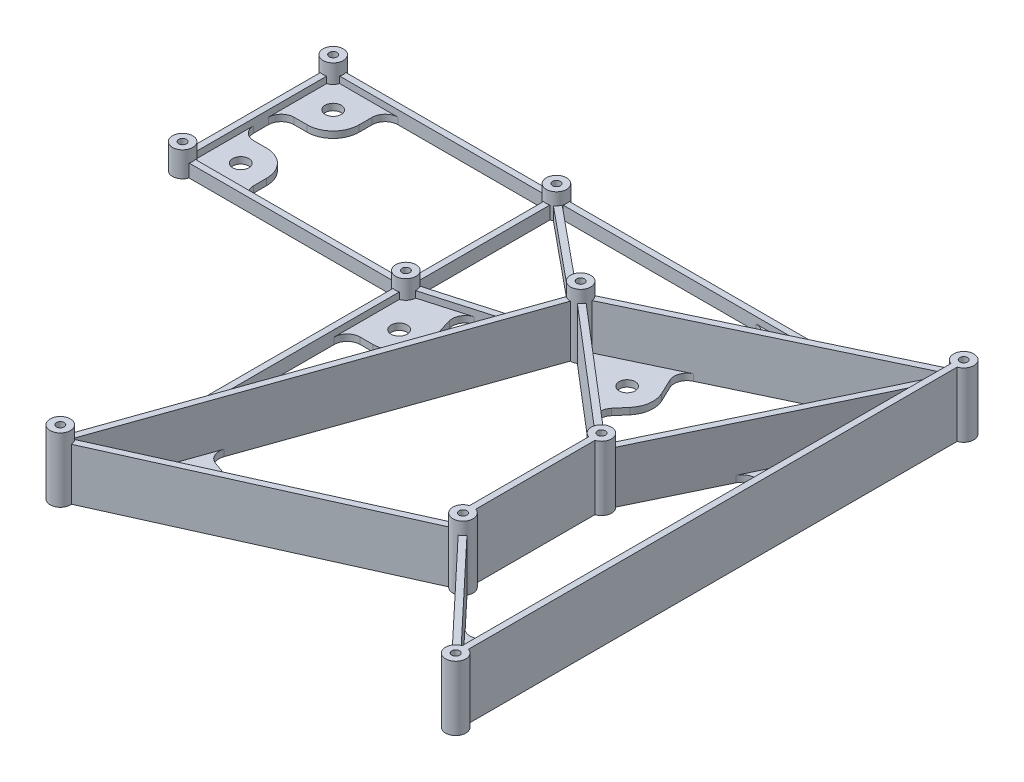
SolidWorks part; units mm, degrees
ref_plane "Front Plane" through (0, 0, 0) normal (0, 0, 1) x (1, 0, 0)
ref_plane "Top Plane" through (0, 0, 0) normal (0, 1, 0) x (1, 0, 0)
ref_plane "Right Plane" through (0, 0, 0) normal (1, 0, 0) x (0, 0, -1)
sketch "Sketch1" plane through (0, 0, 0) normal (0, 1, 0) x (1, 0, 0)
  line L0 (106.9742, -89.6492) -> (106.9742, -142.975) construction
  line L7 (0, -191.1) -> (152.3, -191.1)
  line L8 (152.3, -191.1) -> (152.3, 4.565) construction
  line L9 (106.9742, -89.6492) -> (106.9742, -142.975) construction
  line L10 (0, -191.1) -> (106.9742, -142.975) construction
  line L11 (106.9742, -142.975) -> (152.3, -191.1) construction
  line L12 (52.3, -42.975) -> (106.9742, -89.6492) construction
  line L13 (106.9742, -89.6492) -> (152.3, 4.565) construction
  line L14 (152.3, 4.565) -> (52.3, -42.975) construction
  line L15 (52.3, -42.975) -> (0, -191.1) construction
  line L16 (0, -192.3) -> (152.3, -192.3) construction
  line L17 (0.4923, -192.1944) -> (107.4665, -144.0694)
  line L18 (106.1006, -143.7977) -> (151.4264, -191.9227)
  line L19 (105.7742, -89.6492) -> (105.7742, -142.975)
  line L20 (153.5, -191.1) -> (153.5, 4.565)
  line L21 (108.0556, -90.1694) -> (153.3814, 4.0448)
  line L22 (151.7848, 5.6488) -> (51.7848, -41.8912)
  line L23 (51.5209, -43.8877) -> (106.1951, -90.5619)
  line L24 (51.1685, -42.5755) -> (-1.1315, -190.7005)
  line L25 (0, -189.9) -> (152.3, -189.9) construction
  line L26 (-0.4923, -190.0056) -> (106.4819, -141.8806)
  line L27 (107.8478, -142.1523) -> (153.1736, -190.2773)
  line L28 (108.1742, -89.6492) -> (108.1742, -142.975)
  line L29 (151.1, -191.1) -> (151.1, 4.565)
  line L30 (105.8928, -89.129) -> (151.2186, 5.0852)
  line L31 (152.8152, 3.4812) -> (52.8152, -44.0588)
  line L32 (53.0791, -42.0623) -> (107.7533, -88.7365)
  line L33 (53.4315, -43.3745) -> (1.1315, -191.4995)
  circle A1 centre (0, 0) radius 3.9 construction
  circle A2 centre (52.3, -42.975) radius 1.5
  circle A3 centre (152.3, 4.565) radius 1.5
  circle A4 centre (152.3, -191.1) radius 1.5
  circle A5 centre (0, -191.1) radius 1.5
  circle A6 centre (106.9742, -89.6492) radius 1.5
  circle A7 centre (106.9742, -142.975) radius 1.5
  circle A8 centre (106.9742, -89.6492) radius 3.9
  circle A9 centre (106.9742, -142.975) radius 3.9
  circle A10 centre (152.3, -191.1) radius 3.9
  circle A11 centre (0, -191.1) radius 3.9
  circle A12 centre (52.3, -42.975) radius 3.9
  circle A13 centre (152.3, 4.565) radius 3.9
  dimension "D11" = 3
  dimension "D2" = 4.565
  dimension "D3" = 195.665
  dimension "D4" = 152.3
  dimension "D5" = 52.3
  dimension "D6" = 42.975
  dimension "D7" = 53.3258
  dimension "D8" = 46.6742
  dimension "D9" = 54.6742
  dimension "D10" = 152.3
  dimension "D12" = 2.4
  dimension "D13" = 1.2
  dimension "D14" = 1.2
extrude "Boss-Extrude1" add sketch "Sketch1" along normal blind 20
sketch "Sketch2" plane through (0, 20, 0) normal (0, 1, 0) x (1, 0, 0)
  line L0 (153.5, -187.3892) -> (153.5, 0.8542) construction
  line L1 (151.1, -187.3892) -> (151.1, -0.6973) construction
  line L2 (105.7742, -93.36) -> (105.7742, -139.2642) construction
  line L3 (108.1742, -93.36) -> (108.1742, -139.2642) construction
  line L4 (153.5, -187.3892) -> (153.5, 0.8542)
  line L5 (151.1, -187.3892) -> (151.1, 0.8542)
  line L6 (105.7742, -93.36) -> (105.7742, -139.2642)
  line L7 (108.1742, -93.36) -> (108.1742, -139.2642)
  arc A0 (153.5, 0.8542) -> (148.4334, 4.0555) centre (152.3, 4.565) ccw construction
  arc A1 (55.1361, -40.298) -> (49.933, -46.0746) centre (52.3, -42.975) ccw construction
  arc A2 (108.1742, -93.36) -> (109.6643, -86.8255) centre (106.9742, -89.6492) ccw construction
  arc A3 (110.3919, -144.8536) -> (108.1742, -139.2642) centre (106.9742, -142.975) ccw construction
  arc A4 (148.8823, -189.2214) -> (153.5, -187.3892) centre (152.3, -191.1) ccw construction
  arc A5 (0.1039, -187.2014) -> (3.8764, -190.6719) centre (0, -191.1) ccw construction
  arc A6 (153.5, 0.8542) -> (148.4334, 4.0555) centre (152.3, 4.565) ccw
  arc A7 (55.1361, -40.298) -> (49.933, -46.0746) centre (52.3, -42.975) ccw
  arc A8 (108.1742, -93.36) -> (109.6643, -86.8255) centre (106.9742, -89.6492) ccw
  arc A9 (110.3919, -144.8536) -> (108.1742, -139.2642) centre (106.9742, -142.975) ccw
  arc A10 (148.8823, -189.2214) -> (153.5, -187.3892) centre (152.3, -191.1) ccw
  arc A11 (0.1039, -187.2014) -> (3.8764, -190.6719) centre (0, -191.1) ccw
  circle A12 centre (52.3, -42.975) radius 3.9
  circle A13 centre (152.3, 4.565) radius 3.9
  circle A14 centre (106.9742, -89.6492) radius 3.9
  circle A15 centre (0, -191.1) radius 3.9
  circle A16 centre (106.9742, -142.975) radius 3.9
  circle A17 centre (152.3, -191.1) radius 3.9
  arc M1 (106.6458, -144.4386) -> (106.7177, -144.4529) centre (106.9742, -142.975) cw
  arc M2 (150.8, -191.1) -> (151.1, -190.2) centre (152.3, -191.1) cw
  arc M5 (104.0824, -145.5918) -> (108.6448, -146.4991) centre (106.9742, -142.975) ccw
  arc M7 (148.8823, -189.2214) -> (153.5, -187.3892) centre (152.3, -191.1) ccw
  circle M8 centre (106.9742, -89.6492) radius 1.5
  line M10 (151.1, -0.6973) -> (151.1, -187.3892)
  arc M11 (151.1, -187.3892) -> (150.6294, -187.5759) centre (152.3, -191.1) ccw
  arc M13 (110.3919, -144.8536) -> (108.1742, -139.2642) centre (106.9742, -142.975) ccw
  line M14 (108.1742, -139.2642) -> (108.1742, -93.36)
  arc M15 (108.1742, -93.36) -> (109.6643, -86.8255) centre (106.9742, -89.6492) ccw
  circle M16 centre (152.3, 4.565) radius 1.5
  arc M17 (55.9014, -44.4716) -> (56.1666, -42.4655) centre (52.3, -42.975) ccw
  arc M19 (149.4639, 1.888) -> (149.6099, 1.7413) centre (152.3, 4.565) ccw
  arc M21 (107.5016, -85.785) -> (104.9311, -86.3272) centre (106.9742, -89.6492) ccw
  line M23 (2.367, -188.0004) -> (52.1961, -46.8736)
  arc M24 (52.1961, -46.8736) -> (54.3431, -46.297) centre (52.3, -42.975) ccw
  arc M26 (103.3728, -88.1526) -> (105.7742, -93.36) centre (106.9742, -89.6492) ccw
  line M27 (105.7742, -93.36) -> (105.7742, -139.2642)
  arc M28 (105.7742, -139.2642) -> (103.0978, -143.4031) centre (106.9742, -142.975) ccw
  line M29 (103.0978, -143.4031) -> (2.8918, -188.4832)
  arc M31 (55.1361, -40.298) -> (49.933, -46.0746) centre (52.3, -42.975) ccw
  arc M33 (0.1039, -187.2014) -> (3.8764, -190.6719) centre (0, -191.1) ccw
  arc M35 (148.8823, -189.2214) -> (153.5, -187.3892) centre (152.3, -191.1) ccw
  line M36 (153.5, -187.3892) -> (153.5, 0.8542)
  arc M37 (153.5, 0.8542) -> (148.4334, 4.0555) centre (152.3, 4.565) ccw
  circle M38 centre (52.3, -42.975) radius 1.5
  circle M39 centre (0, -191.1) radius 1.5
extrude "Boss-Extrude2" add sketch "Sketch2" along normal blind 4.8 contours A17 A13 L5 M36 M10 | A13 M37 M19 M16 | A17 M35 M11 M7 M2 | A16 A14 M14 M27 | A16 M5 M13 M28 M1 | A14 M15 M21 M26 M8 | A15 M33 M29 M23 M39 | A12 M24 M17 M31 M38
sketch "Sketch3" plane through (0, 0, 0) normal (0, -1, 0) x (1, 0, 0)
  line L0 (0, 58) -> (0, 0) construction
  line L1 (0, 191.1) -> (0, 58) construction
  line L2 (0, 58) -> (52.3, 42.975) construction
  line L3 (52.3, 42.975) -> (0, 0) construction
  line L4 (0, 0) -> (152.3, 0) construction
  line L5 (-1.2, 191.1) -> (-1.2, 58)
  line L6 (-1.2, 58) -> (-1.2, 0)
  line L7 (-0.3313, 56.8467) -> (49.7736, 42.4522)
  line L8 (49.7736, 42.4522) -> (-0.7618, 0.9271)
  line L9 (0, -1.2) -> (152.3, -1.2)
  line L10 (1.2, 191.1) -> (1.2, 58)
  line L11 (1.2, 58) -> (1.2, 0)
  line L12 (0.3313, 59.1533) -> (54.8264, 43.4978)
  line L13 (54.8264, 43.4978) -> (0.7618, -0.9271)
  line L14 (0, 1.2) -> (152.3, 1.2)
  line L15 (-86, 0) -> (0, 0) construction
  line L16 (-86, 0) -> (-86, 58) construction
  line L17 (-86, 58) -> (0, 58) construction
  line L18 (-84.8, 1.2) -> (0, 1.2)
  line L19 (-84.8, 1.2) -> (-84.8, 56.8)
  line L20 (-84.8, 56.8) -> (0, 56.8)
  line L21 (-87.2, -1.2) -> (0, -1.2)
  line L22 (-87.2, -1.2) -> (-87.2, 59.2)
  line L23 (-87.2, 59.2) -> (0, 59.2)
  circle A0 centre (0, 0) radius 1.5
  circle A1 centre (0, 58) radius 1.5
  circle A2 centre (0, 58) radius 3.9
  circle A3 centre (0, 0) radius 3.9
  circle A4 centre (0, 191.1) radius 1.5 construction
  circle A6 centre (52.3, 42.975) radius 1.5 construction
  circle A7 centre (0, 191.1) radius 1.5
  circle A9 centre (52.3, 42.975) radius 1.5
  arc A11 (54.3431, 46.297) -> (52.1961, 46.8736) centre (52.3, 42.975) ccw construction
  circle A12 centre (-86, 58) radius 3.9
  circle A13 centre (-86, 0) radius 3.9
  circle A14 centre (-86, 58) radius 1.5
  circle A15 centre (-86, 0) radius 1.5
  line M11 (55.1361, 40.298) -> (148.4334, -4.0555)
  arc M12 (148.4334, -4.0555) -> (153.5, -0.8542) centre (152.3, -4.565) ccw
  arc M16 (3.8764, 190.6719) -> (0.1039, 187.2014) centre (0, 191.1) ccw
  line M17 (0.1039, 187.2014) -> (49.933, 46.0746)
  arc M18 (49.933, 46.0746) -> (55.1361, 40.298) centre (52.3, 42.975) ccw
  dimension "D3" = 58
  dimension "D4" = 86
  dimension "D1" = 1.2
  dimension "D2" = 1.2
  dimension "D5" = 1.2
  dimension "D6" = 1.2
extrude "Boss-Extrude3" add sketch "Sketch3" against normal blind 5 separate body contours A2 L10 L5 M17 M16 | A2 L7 L12 M18 | L7 A2 L12 L10 A1 L11 | L12 A2 L10 | L10 A2 L5 A1 L12 | L5 A2 L6 A1 | L6 A2 L11 L7 A1 | L11 A2 L7 | A3 L11 A2 L6 | A3 L13 L8 M18 | L13 A3 L8 L11 L14 | L8 A3 L11 | A0 L14 L11 L8 | L11 A3 L6 A0 L8 | A0 L13 L14 L11 | A0 L11 L14 | L9 A3 L14 L13 A0 | A3 L9 L14 M12 M11 | L14 A3 L13 | L5 A2 L23 | A12 L20 A2 L23 | L6 A3 L18 | L18 A3 L21 A0 L6 | L21 A3 L9 A0 | A13 L21 A3 L18 | A15 L21 A13 L18 L19 L22 | L18 A13 L19 | A15 L22 A13 L21 | A13 L19 A12 L22 | L19 A12 L20 | A14 L22 A12 L19 L20 L23 | A14 L23 A12 L22 | A14 L23 L22 | A15 L22 L21 | L20 A2 L6 | A1 L10 L12 | A1 L7 L11 | A1 L6 L20 | A1 L23 L5 | A0 L18 L6
sketch "Sketch4" plane through (0, 5, 0) normal (0, 1, 0) x (1, 0, 0)
  circle A0 centre (0, -58) radius 1.5
  circle A1 centre (0, 0) radius 1.5 construction
extrude "Cut-Extrude1" cut sketch "Sketch4" against normal through all
sketch "Sketch5" plane through (0, 5, 0) normal (0, 1, 0) x (1, 0, 0)
  circle A0 centre (-86, 0) radius 1.5 construction
  circle A1 centre (-86, -58) radius 1.5 construction
  circle A2 centre (0, -58) radius 1.5 construction
  circle A3 centre (0, 0) radius 1.5 construction
  circle A4 centre (-86, 0) radius 1.5
  circle A5 centre (-86, -58) radius 1.5
  circle A6 centre (0, -58) radius 1.5
  circle A7 centre (0, 0) radius 1.5
  arc A8 (-3.7108, -1.2) -> (-1.2, -3.7108) centre (0, 0) ccw construction
  arc A9 (-3.7108, -59.2) -> (-1.2, -61.7108) centre (0, -58) ccw construction
  arc A10 (-87.2, -54.2892) -> (-82.2892, -59.2) centre (-86, -58) ccw construction
  arc A11 (-82.2892, 1.2) -> (-87.2, -3.7108) centre (-86, 0) ccw construction
  arc A12 (-3.7108, -1.2) -> (-1.2, -3.7108) centre (0, 0) ccw
  arc A13 (-3.7108, -59.2) -> (-1.2, -61.7108) centre (0, -58) ccw
  arc A14 (-87.2, -54.2892) -> (-82.2892, -59.2) centre (-86, -58) ccw
  arc A15 (-82.2892, 1.2) -> (-87.2, -3.7108) centre (-86, 0) ccw
  circle A16 centre (-86, 0) radius 3.9
  circle A17 centre (-86, -58) radius 3.9
  circle A18 centre (0, -58) radius 3.9
  circle A19 centre (0, 0) radius 3.9
  circle M1 centre (0, -58) radius 1.5
  arc M2 (3.2352, -55.822) -> (1.2, -54.2892) centre (0, -58) ccw
  arc M4 (1.2, -3.7108) -> (2.1052, -3.283) centre (0, 0) ccw
  arc M8 (3.6289, -1.4287) -> (3.7108, -1.2) centre (0, 0) ccw
  arc M13 (3.7108, 1.2) -> (-3.7108, 1.2) centre (0, 0) ccw
  arc M15 (-82.2892, 1.2) -> (-87.2, -3.7108) centre (-86, 0) ccw
  arc M17 (-87.2, -54.2892) -> (-82.2892, -59.2) centre (-86, -58) ccw
  arc M19 (-3.7108, -59.2) -> (-1.2, -61.7108) centre (0, -58) ccw
  arc M24 (1.2, -61.7108) -> (3.8979, -58.1287) centre (0, -58) ccw
  circle M28 centre (0, 0) radius 1.5
  circle M29 centre (-86, 0) radius 1.5
  arc M31 (-1.2, -54.2892) -> (-3.7108, -56.8) centre (0, -58) ccw
  arc M33 (-82.2892, -56.8) -> (-84.8, -54.2892) centre (-86, -58) ccw
  arc M35 (-84.8, -3.7108) -> (-82.2892, -1.2) centre (-86, 0) ccw
  arc M37 (-3.7108, -1.2) -> (-1.2, -3.7108) centre (0, 0) ccw
  circle M38 centre (-86, -58) radius 1.5
extrude "Boss-Extrude4" add sketch "Sketch5" along normal blind 4.7 contours A16 M35 M15 M29 | A17 M17 M33 M38 | A18 M24 M2 M31 M19 M1 | A19 M4 M8 M13 M37 M28
sketch "Sketch6" plane through (0, 0, 0) normal (0, 1, 0) x (1, 0, 0)
  line L0 (151.1, -187.3892) -> (151.1, 0.8542) construction
  line L1 (110.3919, -144.8536) -> (150.6294, -187.5759) construction
  line L2 (52.1961, -46.8736) -> (2.367, -188.0004) construction
  line L3 (-82.2892, -56.8) -> (-3.7108, -56.8) construction
  line L4 (1.2, -184.097) -> (1.2, -61.7108) construction
  line L5 (-84.8, -3.7108) -> (-84.8, -54.2892) construction
  line L6 (-82.2892, -1.2) -> (-3.7108, -1.2) construction
  line L7 (3.7108, -1.2) -> (137.3785, -1.2) construction
  line L8 (55.9014, -44.4716) -> (104.9311, -86.3272) construction
  line L9 (148.4334, 4.0555) -> (55.1361, -40.298) construction
  line L10 (11.2, -81.8) -> (1.2, -81.8)
  line L11 (55.9014, -44.4716) -> (104.9311, -86.3272)
  line L12 (20.8112, -69.0388) -> (16.6264, -54.472)
  line L13 (3.8979, -58.1287) -> (49.0648, -45.153) construction
  line L14 (1.2, -184.097) -> (1.2, -61.7108)
  line L15 (3.8979, -58.1287) -> (49.0648, -45.153)
  line L16 (-64.8, -46.8) -> (-64.8, -56.8)
  line L17 (-74.8, -36.8) -> (-84.8, -36.8)
  line L18 (-64.8, -1.2) -> (-64.8, -11.2)
  line L19 (-74.8, -21.2) -> (-84.8, -21.2)
  line L20 (83.0526, -1.2) -> (83.0526, -11.2)
  line L21 (148.4334, 4.0555) -> (55.1361, -40.298)
  line L22 (3.7108, -1.2) -> (137.3785, -1.2)
  line L23 (-82.2892, -56.8) -> (-3.7108, -56.8)
  line L24 (-84.8, -3.7108) -> (-84.8, -54.2892)
  line L25 (-82.2892, -1.2) -> (-3.7108, -1.2)
  line L26 (83.0621, -42.5065) -> (78.0882, -32.044)
  line L27 (149.4639, 1.888) -> (56.1666, -42.4655) construction
  line L28 (81.6363, -53.2927) -> (75.1436, -60.8983)
  line L29 (149.4639, 1.888) -> (56.1666, -42.4655)
  line L30 (88.3147, -24.5249) -> (84.0212, -15.4935)
  line L31 (151.1, -56.8) -> (141.1, -56.8)
  line L32 (126.8742, -51.0531) -> (136.7647, -55.8114)
  line L33 (109.6643, -86.8255) -> (151.1, -0.6973) construction
  line L34 (151.1, -187.3892) -> (151.1, 0.8542)
  line L35 (109.6643, -86.8255) -> (151.1, -0.6973)
  line L36 (126.9642, -162.4493) -> (134.2438, -155.5931)
  line L37 (141.1, -152.8727) -> (151.1, -152.8727)
  line L38 (110.3919, -144.8536) -> (150.6294, -187.5759)
  line L39 (15.744, -150.1139) -> (25.1735, -153.4432)
  line L40 (37.3559, -172.9787) -> (30.9638, -158.77)
  line L41 (2.8918, -188.4832) -> (103.0978, -143.4031) construction
  line L42 (2.8918, -188.4832) -> (103.0978, -143.4031)
  line L43 (52.1961, -46.8736) -> (2.367, -188.0004)
  circle A0 centre (-74.8, -46.8) radius 3.1
  circle A1 centre (21.8441, -162.8727) radius 3.1
  circle A2 centre (141.1, -162.8727) radius 3.1
  circle A3 centre (141.1, -46.8) radius 3.1
  circle A4 centre (-74.8, -11.2) radius 3.1
  circle A5 centre (11.2, -71.8) radius 3.1
  circle A6 centre (74.0307, -46.8) radius 3.1
  circle A7 centre (93.0526, -11.2) radius 3.1
  circle A8 centre (11.2, -71.8) radius 10 construction
  circle A9 centre (21.8441, -162.8727) radius 10 construction
  circle A10 centre (141.1, -162.8727) radius 10 construction
  circle A11 centre (141.1, -46.8) radius 10 construction
  circle A12 centre (74.0307, -46.8) radius 10 construction
  circle A13 centre (93.0526, -11.2) radius 10 construction
  circle A14 centre (-74.8, -11.2) radius 10 construction
  circle A15 centre (-74.8, -46.8) radius 10 construction
  arc A16 (11.2, -81.8) -> (20.8112, -69.0388) centre (11.2, -71.8) ccw
  circle A17 centre (0, -58) radius 3.9 construction
  circle A18 centre (0, -58) radius 3.9
  arc A19 (-74.8, -36.8) -> (-64.8, -46.8) centre (-74.8, -46.8) cw
  arc A20 (-64.8, -11.2) -> (-74.8, -21.2) centre (-74.8, -11.2) cw
  circle A21 centre (-86, -58) radius 3.9 construction
  circle A22 centre (-86, 0) radius 3.9 construction
  circle A23 centre (-86, -58) radius 3.9
  circle A24 centre (-86, 0) radius 3.9
  arc A25 (81.6363, -53.2927) -> (83.0621, -42.5065) centre (74.0307, -46.8) ccw
  circle A26 centre (52.3, -42.975) radius 3.9 construction
  circle A27 centre (52.3, -42.975) radius 3.9
  arc A28 (83.0526, -11.2) -> (84.0212, -15.4935) centre (93.0526, -11.2) ccw
  arc A29 (141.1, -56.8) -> (136.7647, -55.8114) centre (141.1, -46.8) cw
  arc A30 (141.1, -152.8727) -> (134.2438, -155.5931) centre (141.1, -162.8727) ccw
  arc A31 (151.1, -187.3892) -> (153.5, -187.3892) centre (152.3, -191.1) ccw construction
  arc A32 (151.1, -187.3892) -> (153.5, -187.3892) centre (152.3, -191.1) ccw
  arc A33 (30.9638, -158.77) -> (25.1735, -153.4432) centre (21.8441, -162.8727) ccw
  circle A34 centre (0, -191.1) radius 3.9 construction
  circle A35 centre (0, -191.1) radius 3.9
  dimension "D1" = 6.2
  dimension "D3" = 20
  dimension "D2" = 25
extrude "Boss-Extrude5" add sketch "Sketch6" along normal blind 2.5 contours A18 L14 L10 A16 L12 L15 A5 | A23 L23 L16 A19 L17 L24 A0 | A24 L24 L19 A20 L18 L25 A4 | A27 L11 L28 A25 L26 L29 A6 | L20 A28 L30 L21 L22 A7 | A29 L31 L34 L35 L32 A3 | A32 L34 L37 A30 L36 L38 A2 | A35 L42 L40 A33 L39 L43 A1
fillet "Fillet1" radius 5 16 edges at (83.0526, 1.25, 1.2) (88.3147, 1.25, 24.5249) (126.8742, 1.25, 51.0531) (151.1, 1.25, 56.8) (151.1, 1.25, 152.8727) (126.9642, 1.25, 162.4493) (37.3559, 1.25, 172.9787) (15.744, 1.25, 150.1139) (78.0882, 1.25, 32.044) (75.1436, 1.25, 60.8983) (1.2, 1.25, 81.8) (16.6264, 1.25, 54.472) (-64.8, 1.25, 56.8) (-84.8, 1.25, 36.8) (-84.8, 1.25, 21.2) (-64.8, 1.25, 1.2)
